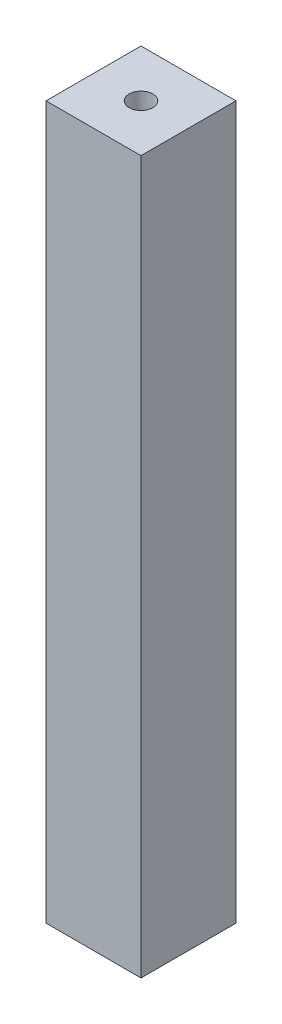
SolidWorks part; units mm, degrees
ref_plane "Front Plane" through (0, 0, 0) normal (0, 0, 1) x (1, 0, 0)
ref_plane "Top Plane" through (0, 0, 0) normal (0, 1, 0) x (1, 0, 0)
ref_plane "Right Plane" through (0, 0, 0) normal (1, 0, 0) x (0, 0, -1)
sketch "Sketch2" plane through (0, 0, 0) normal (0, 1, 0) x (1, 0, 0)
  line L1 (-10, -10) -> (10, -10)
  line L2 (-10, -10) -> (-10, 10)
  line L3 (-10, 10) -> (10, 10)
  line L4 (10, -10) -> (10, 10)
  line L5 (-10, -10) -> (10, 10) construction
  line L6 (-10, 10) -> (10, -10) construction
  circle A0 centre (0, 0) radius 2.5
  point P0 (0, 0)
  dimension "D3" = 5
  dimension "D1" = 20
  dimension "D2" = 20
extrude "Boss-Extrude1" add sketch "Sketch2" along normal blind 150
